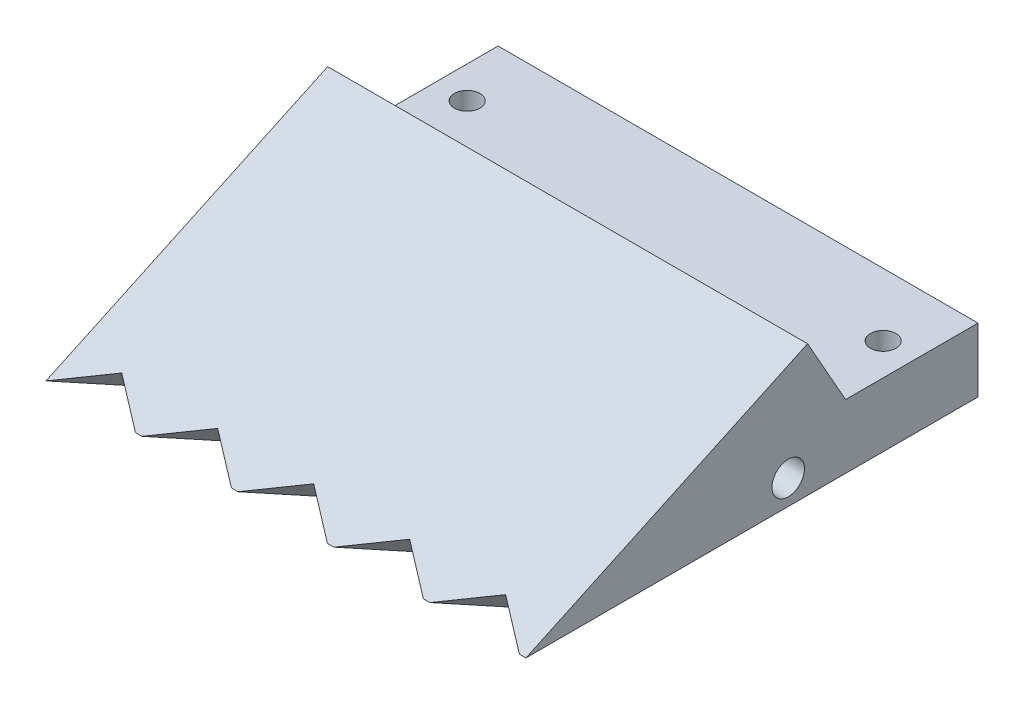
SolidWorks part; units mm, degrees
ref_plane "Front Plane" through (0, 0, 0) normal (0, 0, 1) x (1, 0, 0)
ref_plane "Top Plane" through (0, 0, 0) normal (0, 1, 0) x (1, 0, 0)
ref_plane "Right Plane" through (0, 0, 0) normal (1, 0, 0) x (0, 0, -1)
sketch "Sketch1" plane through (0, 0, 0) normal (1, 0, 0) x (0, 0, -1)
  line L0 (-35.4476, 4.1732) -> (35.2065, 4.1732)
  line L1 (35.2065, 4.1732) -> (35.2065, 14.1732)
  line L2 (35.2065, 14.1732) -> (14.5119, 14.1732)
  line L3 (14.5119, 14.1732) -> (8.5711, 24.6994)
  line L4 (8.5711, 24.6994) -> (-35.4476, 4.1732)
  point P5 (5.8428, 32.0416)
  point P6 (10.4107, 19.5014)
  point P7 (0, 0)
  point P8 (12.6957, 9.2817)
  point P9 (10.687, 16.0506)
  point P10 (10.4733, 15.0987)
  point P11 (-35.4476, 4.1732)
  point P13 (0, 0)
  point P14 (0, 0)
  dimension "D1" = 25
  dimension "D2" = 10
  dimension "D3" = 49.9595
extrude "Boss-Extrude1" add sketch "Sketch1" along normal blind 75
sketch "Sketch2" plane through (0, 14.1732, 0) normal (0, 1, 0) x (1, 0, 0)
  line L0 (0, -11.2894) -> (0, 11.2894) construction
  circle A0 centre (5, 25.3746) radius 2
  circle A1 centre (70, 25.3862) radius 2
  point P4 (3.8254, 25.3861)
  point P5 (5.7144, 25.3865)
  point P6 (0, 0)
  point P7 (4.2726, 25.3862)
  dimension "D1" = 4
  dimension "D2" = 4
  dimension "D3" = 65
  dimension "D4" = 5
extrude "Cut-Extrude1" cut sketch "Sketch2" against normal blind 10
sketch "Sketch3" plane through (0, 0, 0) normal (-1, 0, 0) x (0, 0, 1)
  circle A0 centre (-5.5476, 8.0335) radius 2.543
sketch "Sketch4" plane through (0, 17.0051, 7.9296) normal (0, 0.9063, 0.4226) x (1, 0, 0)
  line L0 (0, -30.3628) -> (7.0659, -25.1031)
  line L1 (0, -11.2894) -> (0, 11.2894) construction
  line L2 (75, -30.3628) -> (0, -30.3628) construction
  line L3 (7.0659, -25.1031) -> (13.9766, -30.3628)
  line L4 (22.0659, -25.1031) -> (28.9766, -30.3628)
  line L5 (15, -30.3628) -> (22.0659, -25.1031)
  line L6 (37.0659, -25.1031) -> (43.9766, -30.3628)
  line L7 (30, -30.3628) -> (37.0659, -25.1031)
  line L8 (52.0659, -25.1031) -> (58.9766, -30.3628)
  line L9 (45, -30.3628) -> (52.0659, -25.1031)
  line L10 (67.0659, -25.1031) -> (73.9766, -30.3628)
  line L11 (60, -30.3628) -> (67.0659, -25.1031)
  line L12 (13.9766, -30.3628) -> (0, -30.3628)
  line L13 (15, -30.3628) -> (28.9766, -30.3628)
  line L14 (43.9766, -30.3628) -> (30, -30.3628)
  line L15 (45, -30.3628) -> (58.9766, -30.3628)
  line L16 (73.9766, -30.3628) -> (60, -30.3628)
  point P8 (0, 0)
  point P20 (13.9766, -30.3628)
  dimension "D1" = 5
extrude "Cut-Extrude2" cut sketch "Sketch4" against normal blind 10
extrude "Cut-Extrude3" cut sketch "Sketch3" against normal blind 100 contours A0
chamfer "Chamfer1" distance 2 angle 45 2 edges at (70, 4.1732, -23.3862) (5, 4.1732, -23.3746)
